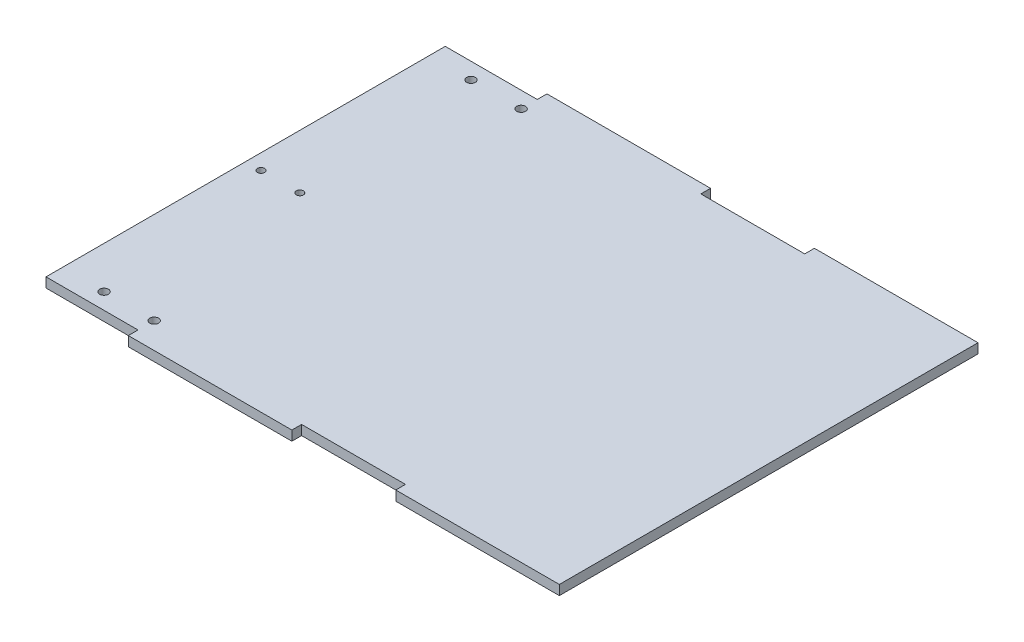
SolidWorks part; units mm, degrees
ref_plane "前基準面" through (0, 0, 0) normal (0, 0, 1) x (1, 0, 0)
ref_plane "上基準面" through (0, 0, 0) normal (0, 1, 0) x (1, 0, 0)
ref_plane "右基準面" through (0, 0, 0) normal (1, 0, 0) x (0, 0, -1)
sketch "草圖1" plane through (0, 0, 0) normal (0, 1, 0) x (1, 0, 0)
  line L0 (-105.4, 97.625) -> (-150.4, 97.625)
  line L4 (-150.4, -97.625) -> (-150.4, 97.625)
  line L5 (150.4, -97.625) -> (-150.4, 97.625) construction
  line L6 (150.4, 97.625) -> (-150.4, -97.625) construction
  line L8 (-105.4, 97.625) -> (-105.4, 102.375)
  line L9 (-105.4, 102.375) -> (-25.4, 102.375)
  line L10 (-25.4, 97.625) -> (-25.4, 102.375)
  line L12 (25.4, 97.625) -> (25.4, 102.375)
  line L13 (25.4, 102.375) -> (105.4, 102.375)
  line L14 (105.4, 97.625) -> (105.4, 102.375)
  line L15 (25.4, 97.625) -> (-25.4, 97.625)
  line L16 (-105.4, -97.625) -> (-150.4, -97.625)
  line L18 (-105.4, -97.625) -> (-105.4, -102.375)
  line L19 (-105.4, -102.375) -> (-25.4, -102.375)
  line L20 (-25.4, -97.625) -> (-25.4, -102.375)
  line L22 (25.4, -97.625) -> (25.4, -102.375)
  line L23 (25.4, -102.375) -> (105.4, -102.375)
  line L24 (105.4, -97.625) -> (105.4, -102.375)
  line L25 (25.4, -97.625) -> (-25.4, -97.625)
  line L26 (105.4, 97.625) -> (105.4, -97.625)
  point P0 (0, 0)
  dimension "D1" = 300.8
  dimension "D2" = 195.25
  dimension "D3" = 4.75
  dimension "D4" = 4.75
  dimension "D5" = 80
  dimension "D6" = 80
  dimension "D7" = 45
  dimension "D8" = 45
  dimension "D9" = 4.75
  dimension "D10" = 4.75
  dimension "D11" = 80
  dimension "D12" = 80
  dimension "D13" = 45
  dimension "D14" = 45
extrude "填料-伸長1" add sketch "草圖1" along normal blind 4.75
sketch "草圖3" plane through (0, 4.75, 0) normal (0, 1, 0) x (1, 0, 0)
  circle A0 centre (-123.9, 0) radius 1.75
  circle A1 centre (-142.9, 0) radius 1.75
extrude "除料-伸長1" cut sketch "草圖3" against normal blind 4.75
sketch "草圖4" plane through (0, 4.75, 0) normal (0, 1, 0) x (1, 0, 0)
  circle A0 centre (-105.4, -89.725) radius 2.15
  circle A1 centre (-129.9, -89.725) radius 2.15
  circle A2 centre (-105.4, 89.725) radius 2.15
  circle A3 centre (-129.9, 89.725) radius 2.15
extrude "除料-伸長2" cut sketch "草圖4" against normal blind 4.75
equation "\"ㄤ\"=300.8"
